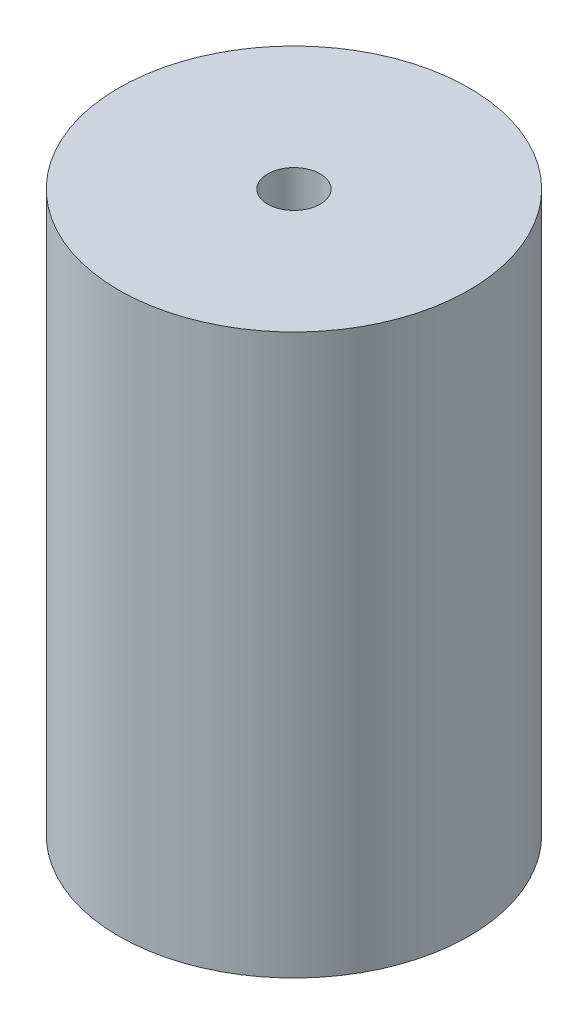
SolidWorks part; units mm, degrees
ref_plane "Front Plane" through (0, 0, 0) normal (0, 0, 1) x (1, 0, 0)
ref_plane "Top Plane" through (0, 0, 0) normal (0, 1, 0) x (1, 0, 0)
ref_plane "Right Plane" through (0, 0, 0) normal (1, 0, 0) x (0, 0, -1)
sketch "Sketch1" plane through (0, 0, 0) normal (0, 1, 0) x (1, 0, 0)
  circle A0 centre (0, 0) radius 10
  circle A1 centre (0, 0) radius 1.5
  dimension "D1" = 20
  dimension "D2" = 3
extrude "Boss-Extrude1" add sketch "Sketch1" along normal blind 31.94
